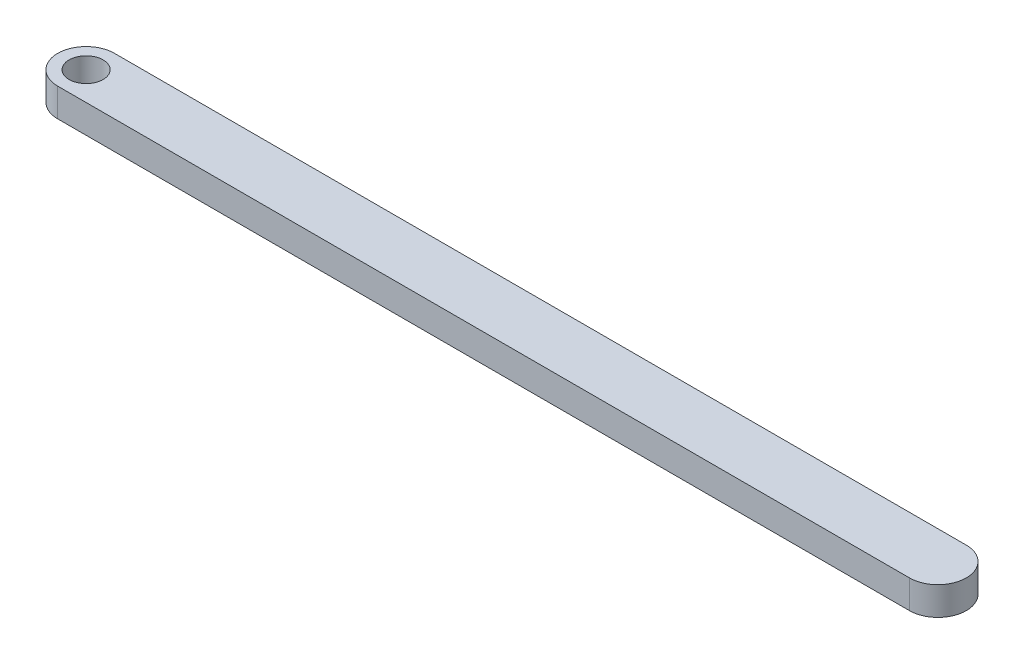
SolidWorks part; units mm, degrees
ref_plane "前视基准面" through (0, 0, 0) normal (0, 0, 1) x (1, 0, 0)
ref_plane "上视基准面" through (0, 0, 0) normal (0, 1, 0) x (1, 0, 0)
ref_plane "右视基准面" through (0, 0, 0) normal (1, 0, 0) x (0, 0, -1)
sketch "草图1" plane through (0, 0, 0) normal (0, 1, 0) x (1, 0, 0)
  line L0 (0, 0) -> (150, 0)
  line L2 (150, -10) -> (0, -10)
  arc A0 (0, 0) -> (0, -10) centre (0, -5) ccw
  arc A1 (150, -10) -> (150, 0) centre (150, -5) ccw
  circle A2 centre (0, -5) radius 3
extrude "凸台-拉伸1" add sketch "草图1" along normal blind 5
